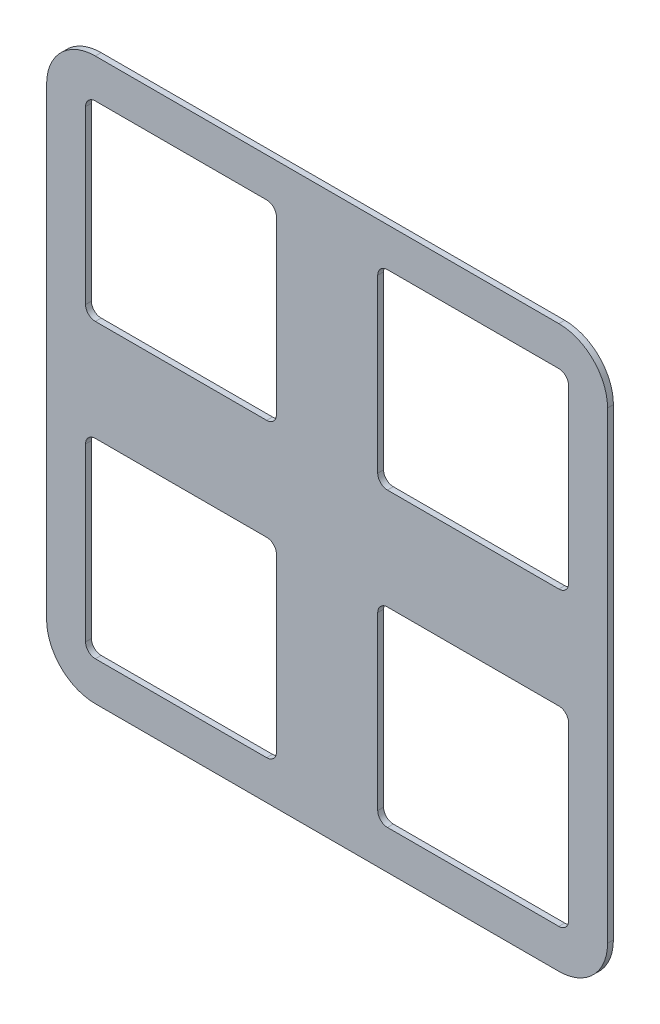
SolidWorks part; units mm, degrees
ref_plane "Front Plane" through (0, 0, 0) normal (0, 0, 1) x (1, 0, 0)
ref_plane "Top Plane" through (0, 0, 0) normal (0, 1, 0) x (1, 0, 0)
ref_plane "Right Plane" through (0, 0, 0) normal (1, 0, 0) x (0, 0, -1)
sketch "Sketch1" plane through (0, 0, 0) normal (0, 0, 1) x (1, 0, 0)
  line L0 (144, 288) -> (144, 50.7239) construction
  line L1 (25, 0) -> (263, 0)
  line L2 (0, 25) -> (0, 263)
  line L3 (25, 288) -> (263, 288)
  line L4 (288, 25) -> (288, 263)
  line L5 (25, 170) -> (113, 170)
  line L6 (20, 175) -> (20, 263)
  line L7 (25, 268) -> (113, 268)
  line L8 (118, 175) -> (118, 263)
  line L9 (288, 144) -> (170.8753, 144) construction
  line L10 (118, 113) -> (118, 25)
  line L11 (25, 20) -> (113, 20)
  line L12 (20, 113) -> (20, 25)
  line L13 (25, 118) -> (113, 118)
  line L14 (263, 118) -> (175, 118)
  line L15 (268, 113) -> (268, 25)
  line L16 (263, 20) -> (175, 20)
  line L17 (170, 113) -> (170, 25)
  line L18 (170, 175) -> (170, 263)
  line L19 (263, 268) -> (175, 268)
  line L20 (268, 175) -> (268, 263)
  line L21 (263, 170) -> (175, 170)
  arc A0 (263, 288) -> (288, 263) centre (263, 263) cw
  arc A1 (25, 0) -> (0, 25) centre (25, 25) cw
  arc A2 (0, 263) -> (25, 288) centre (25, 263) cw
  arc A3 (263, 0) -> (288, 25) centre (263, 25) ccw
  arc A4 (113, 268) -> (118, 263) centre (113, 263) cw
  arc A5 (20, 263) -> (25, 268) centre (25, 263) cw
  arc A6 (25, 170) -> (20, 175) centre (25, 175) cw
  arc A7 (113, 170) -> (118, 175) centre (113, 175) ccw
  arc A8 (113, 118) -> (118, 113) centre (113, 113) cw
  arc A9 (25, 118) -> (20, 113) centre (25, 113) ccw
  arc A10 (20, 25) -> (25, 20) centre (25, 25) ccw
  arc A11 (113, 20) -> (118, 25) centre (113, 25) ccw
  arc A12 (175, 20) -> (170, 25) centre (175, 25) cw
  arc A13 (268, 25) -> (263, 20) centre (263, 25) cw
  arc A14 (263, 118) -> (268, 113) centre (263, 113) cw
  arc A15 (175, 118) -> (170, 113) centre (175, 113) ccw
  arc A16 (175, 170) -> (170, 175) centre (175, 175) cw
  arc A17 (263, 170) -> (268, 175) centre (263, 175) ccw
  arc A18 (268, 263) -> (263, 268) centre (263, 263) ccw
  arc A19 (175, 268) -> (170, 263) centre (175, 263) ccw
  point P9 (0, 0)
  point P12 (0, 288)
  point P15 (288, 0)
  point P24 (20, 268)
  point P27 (20, 170)
  point P30 (118, 170)
  point P46 (118, 118)
  point P47 (20, 118)
  point P48 (20, 20)
  point P71 (268, 20)
  point P72 (268, 118)
  point P73 (170, 118)
  point P74 (170, 170)
  point P75 (268, 170)
  point P76 (268, 268)
  dimension "D3" = 25
  dimension "D6" = 5
  dimension "D1" = 288
  dimension "D2" = 288
  dimension "D4" = 98
  dimension "D5" = 98
extrude "Boss-Extrude1" add sketch "Sketch1" along normal blind 3
